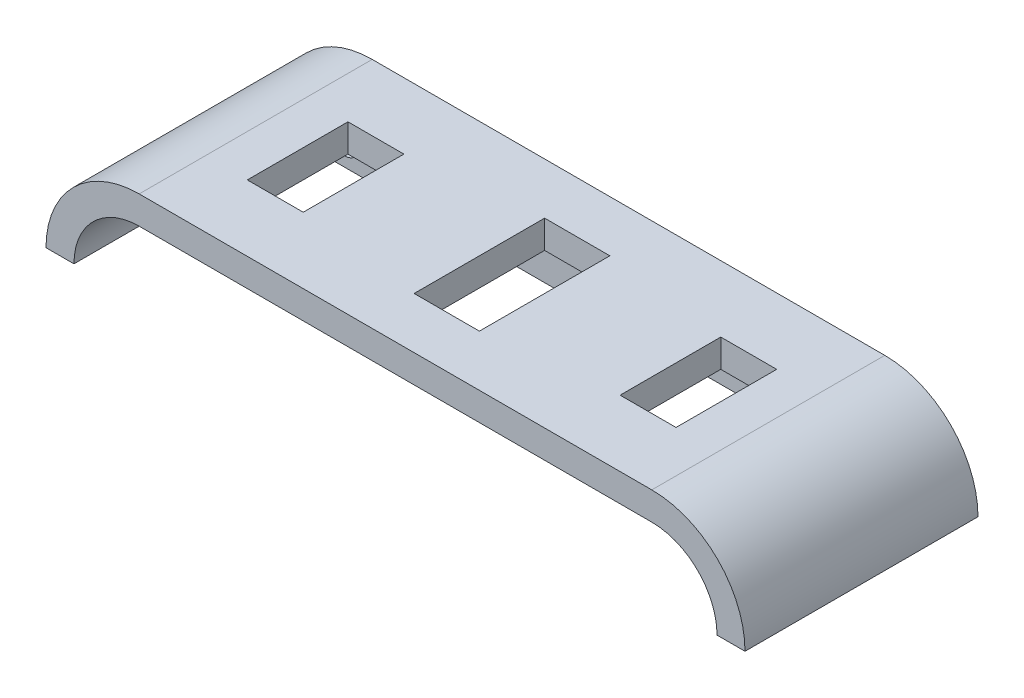
SolidWorks part; units mm, degrees
ref_plane "Plan de face" through (0, 0, 0) normal (0, 0, 1) x (1, 0, 0)
ref_plane "Plan de dessus" through (0, 0, 0) normal (0, 1, 0) x (1, 0, 0)
ref_plane "Plan de droite" through (0, 0, 0) normal (1, 0, 0) x (0, 0, -1)
sketch "Esquisse1" plane through (0, 0, 0) normal (0, 0, 1) x (1, 0, 0)
  line L0 (-54.2252, 16.4537) -> (0.7748, 16.4537)
  line L1 (-64.2252, 6.4537) -> (-61.2252, 6.4537)
  line L2 (-54.2252, 13.4537) -> (0.7748, 13.4537)
  line L3 (10.7748, 6.4537) -> (7.7748, 6.4537)
  arc A0 (-64.2252, 6.4537) -> (-54.2252, 16.4537) centre (-54.2252, 6.4537) cw
  arc A1 (0.7748, 16.4537) -> (10.7748, 6.4537) centre (0.7748, 6.4537) cw
  arc A2 (-61.2252, 6.4537) -> (-54.2252, 13.4537) centre (-54.2252, 6.4537) cw
  arc A3 (7.7748, 6.4537) -> (0.7748, 13.4537) centre (0.7748, 6.4537) ccw
extrude "Boss.-Extru.1" add sketch "Esquisse1" along normal blind 25
sketch "Esquisse3" plane through (0, 0, 0) normal (0, 0, 1) x (1, 0, 0)
  line L0 (-61.0626, 7.9537) -> (7.6122, 7.9537)
  line L1 (-54.2252, 13.4537) -> (0.7748, 13.4537)
  line L2 (-54.2252, 13.4537) -> (0.7748, 13.4537) construction
  arc A0 (-61.0626, 7.9537) -> (-54.2252, 13.4537) centre (-54.2252, 6.4537) cw
  arc A1 (7.6122, 7.9537) -> (0.7748, 13.4537) centre (0.7748, 6.4537) ccw
  arc A2 (-54.2252, 13.4537) -> (-61.2252, 6.4537) centre (-54.2252, 6.4537) ccw construction
  arc A3 (7.7748, 6.4537) -> (0.7748, 13.4537) centre (0.7748, 6.4537) ccw construction
extrude "Boss.-Extru.2" add sketch "Esquisse3" along normal blind 3
sketch "Esquisse5" plane through (0, 16.4537, 0) normal (0, 1, 0) x (1, 0, 0)
  line L0 (-26.7252, -25) -> (-26.7252, 0) construction
  line L1 (0.7748, -25) -> (-54.2252, -25) construction
  line L2 (0.7748, 0) -> (-54.2252, 0) construction
  line L3 (0.7748, -12.5) -> (-54.2252, -12.5) construction
  line L4 (0.7748, -25) -> (0.7748, 0) construction
  line L5 (-54.2252, -25) -> (-54.2252, 0) construction
  line L6 (-49.7252, -17.9) -> (-43.7252, -17.9)
  line L7 (-3.7252, -7.1) -> (-9.7252, -7.1)
  line L8 (-3.7252, -7.1) -> (-3.7252, -17.9)
  line L9 (-3.7252, -17.9) -> (-9.7252, -17.9)
  line L10 (-9.7252, -7.1) -> (-9.7252, -17.9)
  line L11 (-3.7252, -7.1) -> (-9.7252, -17.9) construction
  line L12 (-3.7252, -17.9) -> (-9.7252, -7.1) construction
  line L13 (-43.7252, -7.1) -> (-43.7252, -17.9)
  line L14 (-49.7252, -7.1) -> (-43.7252, -7.1)
  line L15 (-49.7252, -7.1) -> (-49.7252, -17.9)
  line L17 (-23.2252, -5.5) -> (-30.2252, -5.5)
  line L18 (-23.2252, -5.5) -> (-23.2252, -19.5)
  line L19 (-23.2252, -19.5) -> (-30.2252, -19.5)
  line L20 (-30.2252, -5.5) -> (-30.2252, -19.5)
  line L21 (-23.2252, -5.5) -> (-30.2252, -19.5) construction
  line L22 (-23.2252, -19.5) -> (-30.2252, -5.5) construction
  point P12 (-6.7252, -12.5)
  point P21 (-26.7252, -12.5)
  dimension "D1" = 6
  dimension "D2" = 10.8
  dimension "D3" = 20
  dimension "D4" = 7
  dimension "D5" = 14
extrude "Enlèv. mat.-Extru.1" cut sketch "Esquisse5" against normal blind 13
sketch "Esquisse6" plane through (0, 0, 0) normal (0, 0, -1) x (-1, 0, 0)
  line L0 (26.7252, 13.4537) -> (26.7252, 7.9537) construction
  line L1 (54.2252, 10.7037) -> (26.7252, 10.7037) construction
  line L2 (61.0626, 7.9537) -> (-7.6122, 7.9537) construction
  line L3 (54.2252, 13.4537) -> (-0.7748, 13.4537) construction
  circle A0 centre (-0.7748, 10.7037) radius 1.7
  circle A1 centre (26.7252, 10.7037) radius 1.7
  circle A2 centre (54.2252, 10.7037) radius 1.7
  dimension "D1" = 3.4
  dimension "D2" = 27.5
  dimension "D3" = 3.4
extrude "Enlèv. mat.-Extru.2" cut sketch "Esquisse6" against normal blind 13
